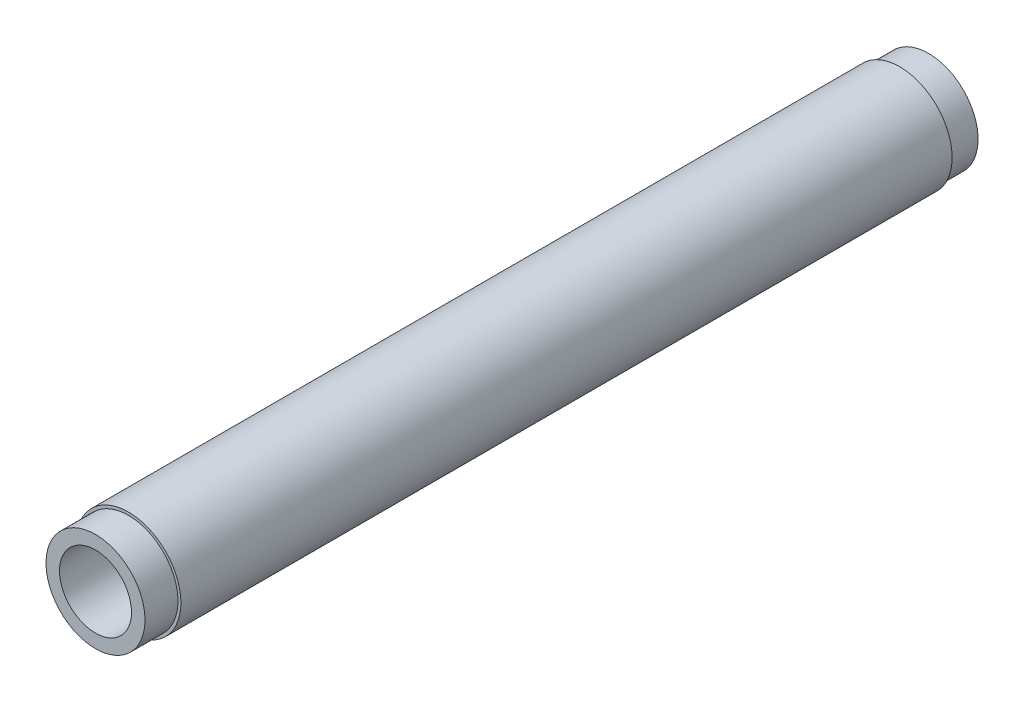
SolidWorks part; units mm, degrees
ref_plane "Front Plane" through (0, 0, 0) normal (0, 0, 1) x (1, 0, 0)
ref_plane "Top Plane" through (0, 0, 0) normal (0, 1, 0) x (1, 0, 0)
ref_plane "Right Plane" through (0, 0, 0) normal (1, 0, 0) x (0, 0, -1)
sketch "Sketch1" plane through (0, 0, 0) normal (0, 0, 1) x (1, 0, 0)
  circle A2 centre (159.099, 159.099) radius 6 construction
  circle A3 centre (159.099, 159.099) radius 6
extrude "Extrude1" add sketch "Sketch1" along normal blind 45 and the other way blind 56
sketch "Sketch2" plane through (0, 0, 0) normal (0, 0, 1) x (1, 0, 0)
  circle A0 centre (159.099, 159.099) radius 6.35
  circle A1 centre (30.0312, 126.9975) radius 6.35 construction
extrude "Extrude2" add sketch "Sketch2" along normal up to surface (41 mm away) and the other way up to surface (52.5 mm away)
sketch "Sketch3" plane through (0, 0, 0) normal (0, 0, 1) x (1, 0, 0)
  circle A0 centre (159.099, 159.099) radius 4.365
  circle A2 centre (30.0312, 126.9975) radius 4.365 construction
  circle A3 centre (159.099, 159.099) radius 6 construction
extrude "Cut-Extrude1" cut sketch "Sketch3" against normal through all and the other way through all
